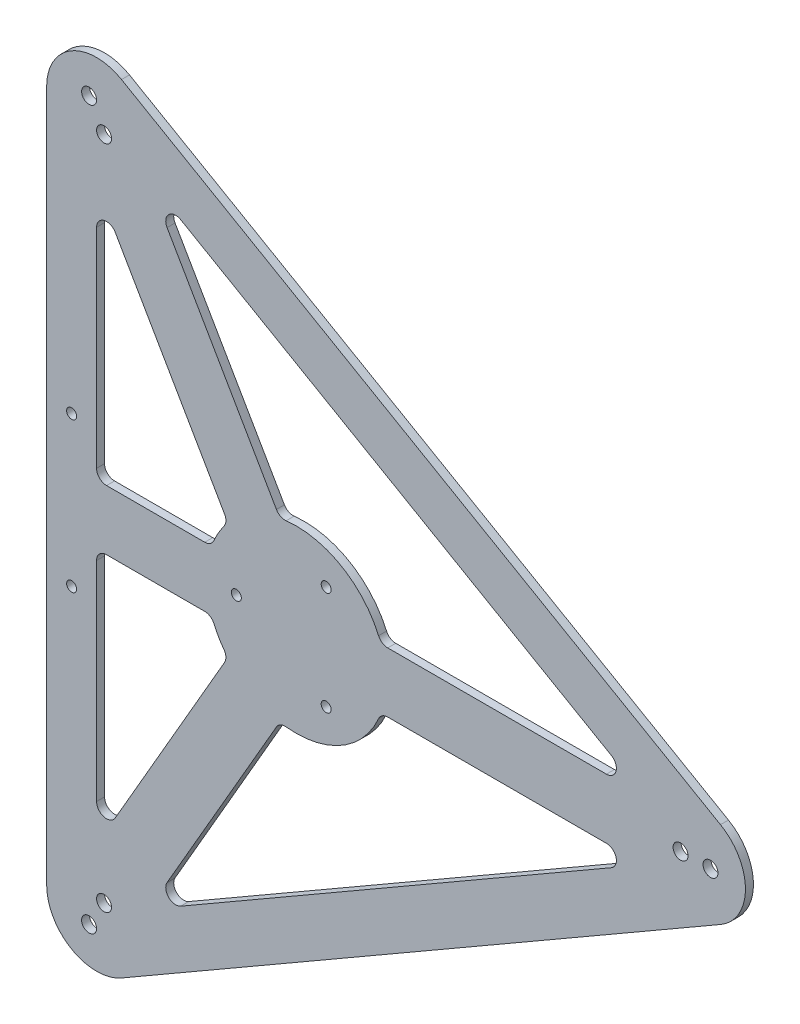
SolidWorks part; units mm, degrees
other "Frame1"
material "Hexcel AS4C (3000 Filaments)"
ref_plane "Front" through (0, 0, 0) normal (0, 0, 1) x (1, 0, 0)
ref_plane "Top" through (0, 0, 0) normal (0, 1, 0) x (1, 0, 0)
ref_plane "Right" through (0, 0, 0) normal (1, 0, 0) x (0, 0, -1)
sketch "BoardSke" plane through (0, 0, 0) normal (0, 0, 1) x (1, 0, 0)
  line L1 (42.5, 4.3301) -> (-17.5, 38.9711)
  line L2 (-25, 34.641) -> (-25, -34.641)
  line L3 (-17.5, -38.9711) -> (42.5, -4.3301)
  circle A0 centre (0, 0) radius 25 construction
  arc A1 (-25, -34.641) -> (-17.5, -38.9711) centre (-20, -34.641) ccw
  arc A2 (42.5, 4.3301) -> (42.5, -4.3301) centre (40, 0) cw
  arc A3 (-17.5, 38.9711) -> (-25, 34.641) centre (-20, 34.641) ccw
  dimension "D1" = 50
  dimension "D2" = 5
extrude "Board" add sketch "BoardSke" along normal blind 0.8 separate body
sketch "CutSke" plane through (0, 0, 0.8) normal (0, 0, 1) x (1, 0, 0)
  line L0 (31.0718, 3) -> (9.1652, 3)
  line L1 (31.5718, 4.866) -> (-11.5718, 29.775)
  line L2 (-12.9378, 28.409) -> (-1.9845, 9.4373)
  line L3 (0, 0) -> (-22.5, 38.9711) construction
  line L4 (0, 0) -> (45, 0) construction
  line L5 (0, 0) -> (-22.5, -38.9711) construction
  line L6 (42.5, 4.3301) -> (-17.5, 38.9711) construction
  line L7 (31.0718, -3) -> (9.1652, -3)
  line L8 (-11.5718, -29.775) -> (31.5718, -4.866)
  line L9 (-12.9378, -28.409) -> (-1.9845, -9.4373)
  line L10 (-18.134, -25.409) -> (-7.1807, -6.4373)
  line L11 (-20, 24.909) -> (-20, -24.909)
  line L12 (-18.134, 25.409) -> (-7.1807, 6.4373)
  arc A0 (8.2486, 3.6) -> (-1.0066, 8.9435) centre (0, 0) ccw
  arc A1 (-17.5, 38.9711) -> (-25, 34.641) centre (-20, 34.641) ccw construction
  arc A2 (42.5, -4.3301) -> (42.5, 4.3301) centre (40, 0) ccw construction
  arc A3 (-25, -34.641) -> (-17.5, -38.9711) centre (-20, -34.641) ccw construction
  arc A4 (31.0718, 3) -> (31.5718, 4.866) centre (31.0718, 4) ccw
  arc A5 (-11.5718, 29.775) -> (-12.9378, 28.409) centre (-12.0718, 28.909) ccw
  arc A6 (-1.9845, 9.4373) -> (-1.0066, 8.9435) centre (-1.1185, 9.9373) ccw
  arc A7 (9.1652, 3) -> (8.2486, 3.6) centre (9.1652, 4) cw
  arc A8 (-1.0066, -8.9435) -> (8.2486, -3.6) centre (0, 0) ccw
  arc A9 (-1.9845, -9.4373) -> (-1.0066, -8.9435) centre (-1.1185, -9.9373) cw
  arc A10 (9.1652, -3) -> (8.2486, -3.6) centre (9.1652, -4) ccw
  arc A11 (31.5718, -4.866) -> (31.0718, -3) centre (31.0718, -4) ccw
  arc A12 (-12.9378, -28.409) -> (-11.5718, -29.775) centre (-12.0718, -28.909) ccw
  arc A13 (-7.242, 5.3435) -> (-7.242, -5.3435) centre (0, 0) ccw
  arc A14 (-7.1807, 6.4373) -> (-7.242, 5.3435) centre (-8.0467, 5.9373) cw
  arc A15 (-7.1807, -6.4373) -> (-7.242, -5.3435) centre (-8.0467, -5.9373) ccw
  arc A16 (-20, -24.909) -> (-18.134, -25.409) centre (-19, -24.909) ccw
  arc A17 (-18.134, 25.409) -> (-20, 24.909) centre (-19, 24.909) ccw
  point P55 (0, 0)
  dimension "D1" = 18
  dimension "D5" = 1
  dimension "D6" = 1
  dimension "D2" = 3
  dimension "D3" = 3
  dimension "D4" = 5
  dimension "D7" = 3
extrude "Cut" cut sketch "CutSke" against normal through all
sketch "HolesSke" plane through (0, 0, 0.8) normal (0, 0, 1) x (1, 0, 0)
  circle A0 centre (-6, 0) radius 0.5
  circle A1 centre (3, 5.1962) radius 0.5
  circle A2 centre (3, -5.1962) radius 0.5
  point P9 (0, 0)
  dimension "D2" = 6
  dimension "D1" = 1
  dimension "D3" = 3
extrude "Holes" cut sketch "HolesSke" against normal through all
sketch "Holes2Ske" plane through (0, 0, 0.8) normal (0, 0, 1) x (1, 0, 0)
  line L0 (38.5, 0) -> (41.5, 0) construction
  line L1 (0, 0) -> (40, 0) construction
  circle A1 centre (38.5, 0) radius 0.75
  circle A2 centre (41.5, 0) radius 0.75
  circle A3 centre (-19.25, -33.342) radius 0.75
  circle A4 centre (-20.75, -35.9401) radius 0.75
  circle A5 centre (-19.25, 33.342) radius 0.75
  circle A6 centre (-20.75, 35.9401) radius 0.75
  point P7 (40, 0)
  point P18 (0, 0)
  dimension "D1" = 40
  dimension "D2" = 1.5
  dimension "D3" = 3
  dimension "D4" = 3
extrude "Holes2" cut sketch "Holes2Ske" against normal through all
sketch "Holes3Ske" plane through (0, 0, 0.8) normal (0, 0, 1) x (1, 0, 0)
  line L0 (-25, 34.641) -> (-25, -34.641) construction
  line L1 (-25, 0) -> (-20, 0) construction
  line L2 (-20, 24.909) -> (-20, -24.909) construction
  line L3 (-22.5, 7.5) -> (-22.5, -7.5) construction
  circle A0 centre (-22.5, 7.5) radius 0.5
  circle A1 centre (-22.5, -7.5) radius 0.5
  circle A2 centre (-6, 0) radius 0.5 construction
  point P8 (-22.5, 0)
  dimension "D1" = 15
extrude "Holes3" cut sketch "Holes3Ske" against normal through all
sketch "ReinforceSke" plane through (0, 0, 0) normal (0, 0, 1) x (1, 0, 0)
  line L0 (-9.1652, 3) -> (-19, 3)
  line L1 (-20, 24.909) -> (-20, -24.909) construction
  line L3 (-19, -3) -> (-9.1652, -3)
  line L4 (9.1652, 3) -> (31.0718, 3) construction
  line L5 (31.0718, -3) -> (9.1652, -3) construction
  line L6 (-20, 4) -> (-20, -4)
  arc A2 (-20, 4) -> (-19, 3) centre (-19, 4) ccw
  arc A3 (-19, -3) -> (-20, -4) centre (-19, -4) ccw
  arc A4 (-7.242, 5.3435) -> (-7.1807, 6.4373) centre (-8.0467, 5.9373) ccw construction
  arc A5 (-9.1652, 3) -> (-8.2486, 3.6) centre (-9.1652, 4) ccw
  arc A6 (-7.242, 5.3435) -> (-7.242, -5.3435) centre (0, 0) ccw construction
  arc A7 (-9.1652, -3) -> (-8.2486, -3.6) centre (-9.1652, -4) cw
  arc A8 (-8.2486, -3.6) -> (-8.2486, 3.6) centre (0, 0) cw
extrude "Reinforce" add sketch "ReinforceSke" along normal up to vertex (0.8 mm away)
